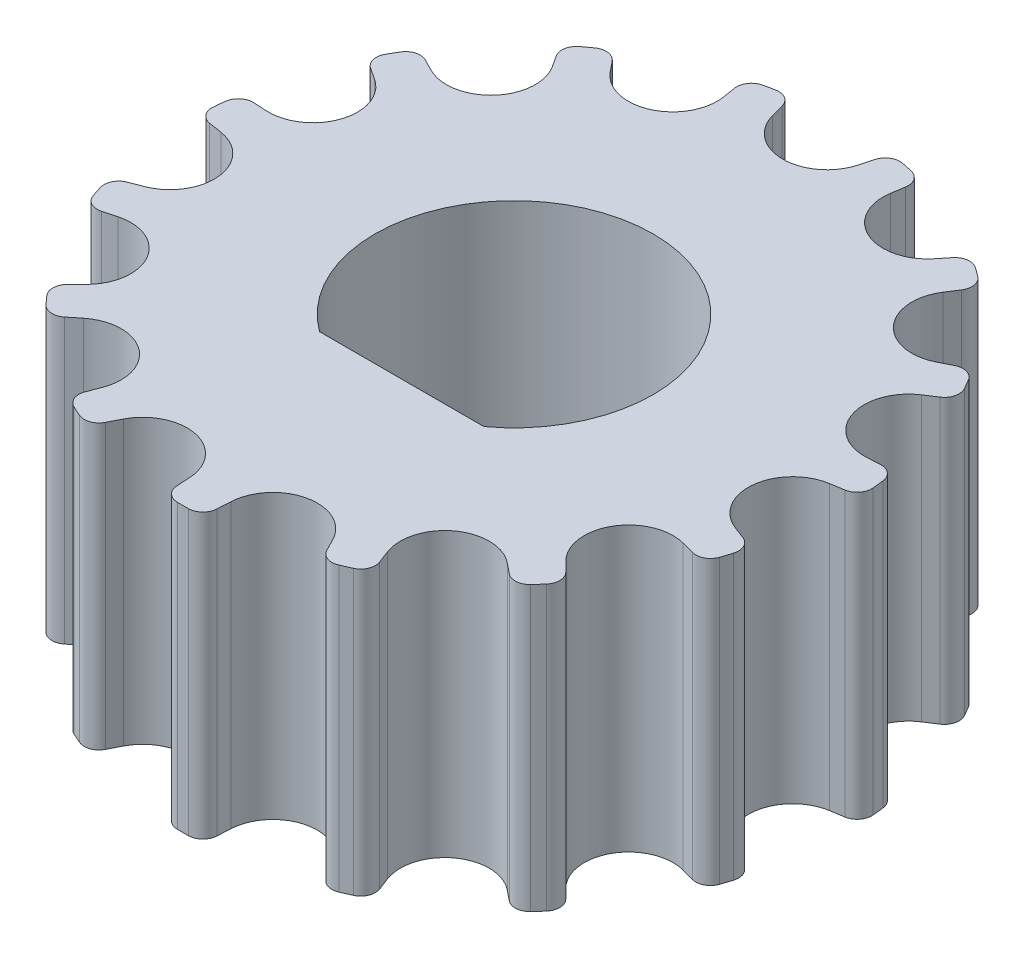
SolidWorks part; units mm, degrees
ref_plane "Front Plane" through (0, 0, 0) normal (0, 0, 1) x (1, 0, 0)
ref_plane "Top Plane" through (0, 0, 0) normal (0, 1, 0) x (1, 0, 0)
ref_plane "Right Plane" through (0, 0, 0) normal (1, 0, 0) x (0, 0, -1)
sketch "Sketch1" plane through (0, 0, 0) normal (0, 1, 0) x (1, 0, 0)
  circle A0 centre (0, 0) radius 7.162
  dimension "D1" = 14.3239
extrude "Boss-Extrude1" add sketch "Sketch1" along normal blind 5.8
sketch "Sketch2" plane through (0, 5.8, 0) normal (0, 1, 0) x (1, 0, 0)
  line L0 (0, 0) -> (0, 7.162) construction
  line L1 (-0.8787, 6.1745) -> (-0.95, 6.4393)
  line L2 (-2.7581, 6.1947) -> (-2.7581, 7.162)
  line L3 (-2.7581, 7.162) -> (2.7581, 7.162)
  line L4 (0.8787, 6.1745) -> (0.95, 6.4393)
  line L5 (2.7581, 6.1947) -> (2.7581, 7.162)
  circle A0 centre (0, 0) radius 7.162 construction
  arc A1 (0.8787, 6.1745) -> (-0.8787, 6.1745) centre (0, 6.411) cw
  arc A2 (-0.95, 6.4393) -> (-1.2971, 6.6558) centre (-1.2397, 6.3613) ccw
  circle A3 centre (0, 0) radius 6.781 construction
  arc A4 (0.95, 6.4393) -> (1.2971, 6.6558) centre (1.2397, 6.3613) cw
  arc A5 (-1.2971, 6.6558) -> (-2.7581, 6.1947) centre (0, 0) ccw
  arc A6 (1.2971, 6.6558) -> (2.7581, 6.1947) centre (0, 0) cw
  point P11 (0, 6.781)
  point P19 (0, 5.501)
  dimension "D1" = 13.5619
  dimension "D3" = 0.3
  dimension "D5" = 0.91
  dimension "D2" = 0.95
  dimension "D4" = 1.28
  dimension "D6" = 24
extrude "Cut-Extrude1" cut sketch "Sketch2" against normal through all
pattern_circular "CirPattern1" count 15 over 360 about axis through (0, 0, 0) along (0, 1, 0) of "Cut-Extrude1"
sketch "Sketch3" plane through (0, 0, 0) normal (0, -1, 0) x (1, 0, 0)
  line L0 (1.683, 2.3) -> (-1.683, 2.3)
  arc A0 (-1.683, 2.3) -> (1.683, 2.3) centre (0, 0) ccw
  dimension "D1" = 5.7
  dimension "D2" = 2.3
extrude "Cut-Extrude2" cut sketch "Sketch3" against normal through all
equation "\"smallPulleyTeeth\"= 15"
equation "\"largePulleyTeeth\"= 30"
equation "\"eighthThick\"= 2.9mm"
equation "\"bushingDiam\"= 7.85mm"
equation "\"D1@Sketch1\"=3*\"smallPulleyTeeth\"/pi"
equation "\"D1@Boss-Extrude1\" = \"eighthThick\" * 2"
equation "\"D1@Sketch2\"=3*\"smallPulleyTeeth\"/pi-0.762mm"
equation "\"D6@Sketch2\"=360/\"smallPulleyTeeth\""
equation "\"quarterThick\"=5.6mm"
equation "\"D1@CirPattern1\"=\"smallPulleyTeeth\""
